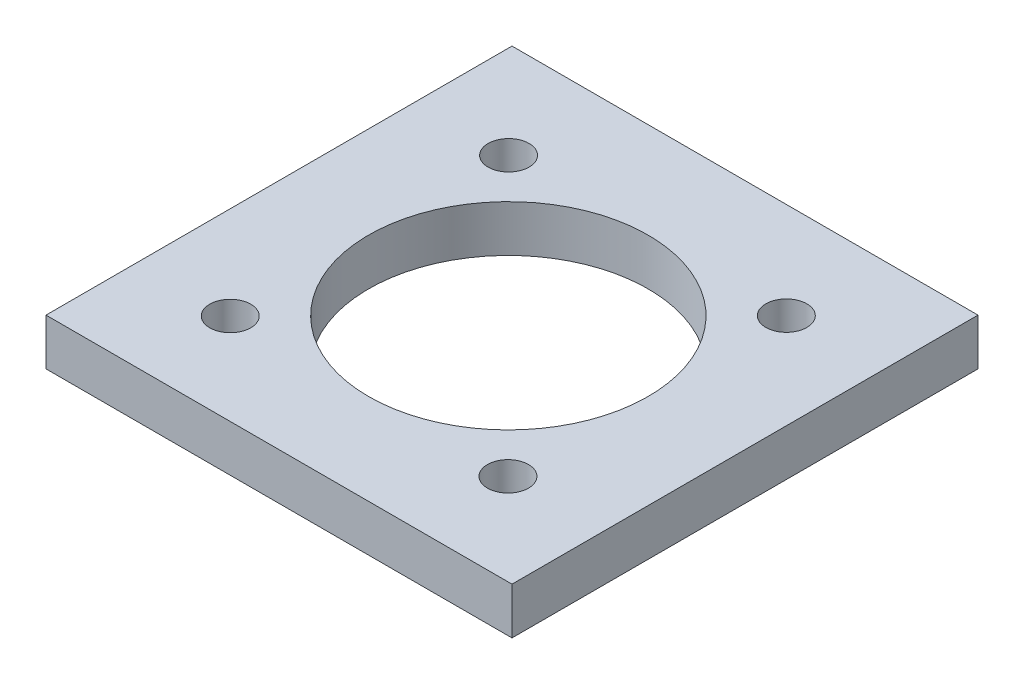
SolidWorks part; units mm, degrees
ref_plane "Alzado" through (0, 0, 0) normal (0, 0, 1) x (1, 0, 0)
ref_plane "Planta" through (0, 0, 0) normal (0, 1, 0) x (1, 0, 0)
ref_plane "Vista lateral" through (0, 0, 0) normal (1, 0, 0) x (0, 0, -1)
sketch "Croquis1" plane through (0, 0, 0) normal (0, 1, 0) x (1, 0, 0)
  line L1 (25, -25) -> (-25, -25)
  line L2 (25, -25) -> (25, 25)
  line L3 (25, 25) -> (-25, 25)
  line L4 (-25, -25) -> (-25, 25)
  line L5 (25, -25) -> (-25, 25) construction
  line L6 (25, 25) -> (-25, -25) construction
  point P0 (0, 0)
  point P6 (0, 0)
  dimension "D1" = 50
  dimension "D2" = 50
extrude "Saliente-Extruir1" add sketch "Croquis1" along normal blind 5 contours L2 L1 L4 L3
sketch "Croquis2" plane through (0, 5, 0) normal (0, 1, 0) x (1, 0, 0)
  line L0 (-0.1328, 19.577) -> (-0.1328, -20.0988) construction
  line L1 (-19.9328, -20.0988) -> (19.6672, -20.0988)
  line L2 (-19.9328, -20.0988) -> (-19.9328, 19.577)
  line L3 (-19.9328, 19.577) -> (19.6672, 19.577)
  line L4 (19.6672, -20.0988) -> (19.6672, 19.577)
  line L5 (-19.9328, -20.0988) -> (19.6672, 19.577) construction
  line L6 (-19.9328, 19.577) -> (19.6672, -20.0988) construction
  line L7 (16.9672, 14.6676) -> (19.6672, 14.6676) construction
  line L8 (14.7672, 16.8676) -> (14.7672, 19.577) construction
  circle A0 centre (-0.1328, -0.2609) radius 15
  circle A1 centre (14.7672, 14.6676) radius 2.2
  circle A2 centre (-15.0328, 14.6676) radius 2.2
  circle A3 centre (-15.0328, -15.1988) radius 2.2
  circle A4 centre (14.7672, -15.1988) radius 2.2
  point P0 (7.3471, -0.2988)
  dimension "D1" = 30
  dimension "D2" = 4.4
  dimension "D3" = 2.7
  dimension "D4" = 2.7094
extrude "Cortar-Extruir1" cut sketch "Croquis2" against normal blind 5 contours A0 | A1 | A3 | A2 | A4
